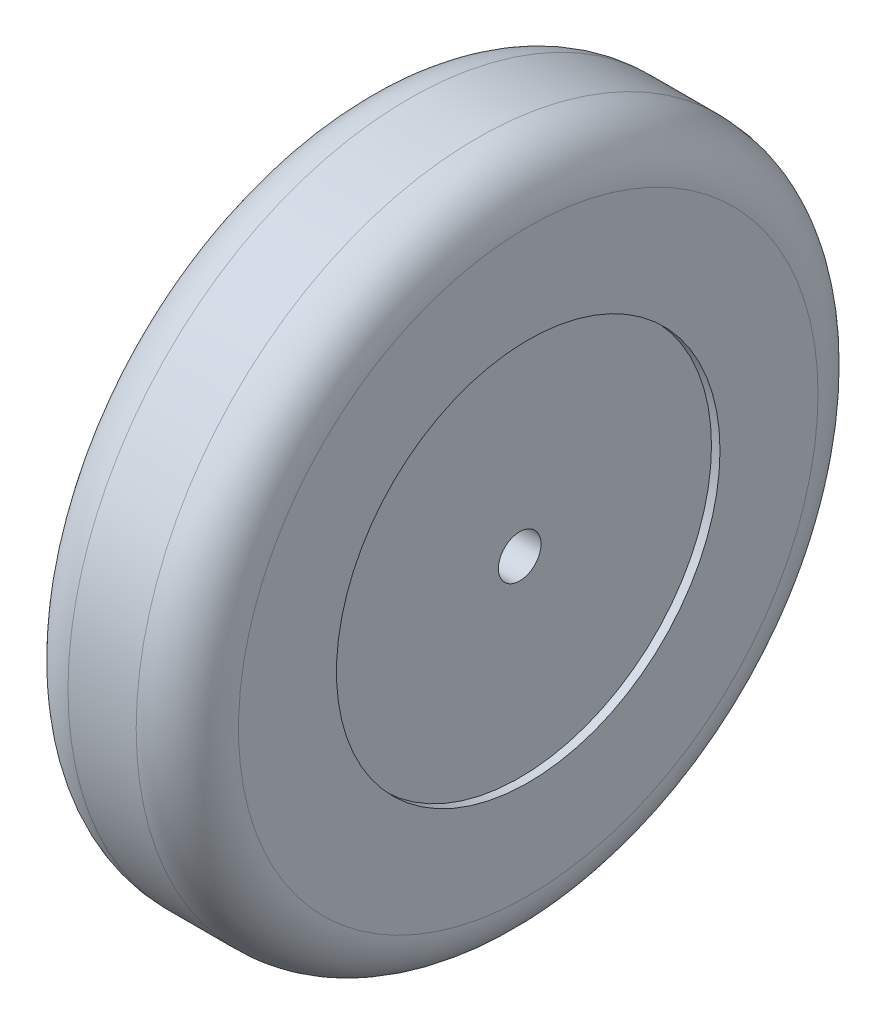
SolidWorks part; units mm, degrees
ref_plane "Front Plane" through (0, 0, 0) normal (0, 0, 1) x (1, 0, 0)
ref_plane "Top Plane" through (0, 0, 0) normal (0, 1, 0) x (1, 0, 0)
ref_plane "Right Plane" through (0, 0, 0) normal (1, 0, 0) x (0, 0, -1)
sketch "Sketch1" plane through (0, 0, 0) normal (1, 0, 0) x (0, 0, -1)
  circle A0 centre (0, 0) radius 50.8
  dimension "D1" = 101.6
extrude "Boss-Extrude1" add sketch "Sketch1" along normal mid plane 25.4
sketch "Sketch2" plane through (12.7, 0, 0) normal (1, 0, 0) x (0, 0, -1)
  circle A0 centre (0, 0) radius 3.175
  dimension "D1" = 6.35
extrude "Cut-Extrude1" cut sketch "Sketch2" against normal through all
fillet "Fillet1" radius 7.62 2 edges at (-12.7, 0, -50.8) (12.7, 0, -50.8)
sketch "Sketch3" plane through (12.7, 0, 0) normal (1, 0, 0) x (0, 0, -1)
  circle A0 centre (0, 0) radius 28.575
  dimension "D1" = 57.15
extrude "Cut-Extrude2" cut sketch "Sketch3" against normal blind 1.27
mirror "Mirror1" about plane through (0, 0, 0) normal (1, 0, 0) of "Cut-Extrude2"
